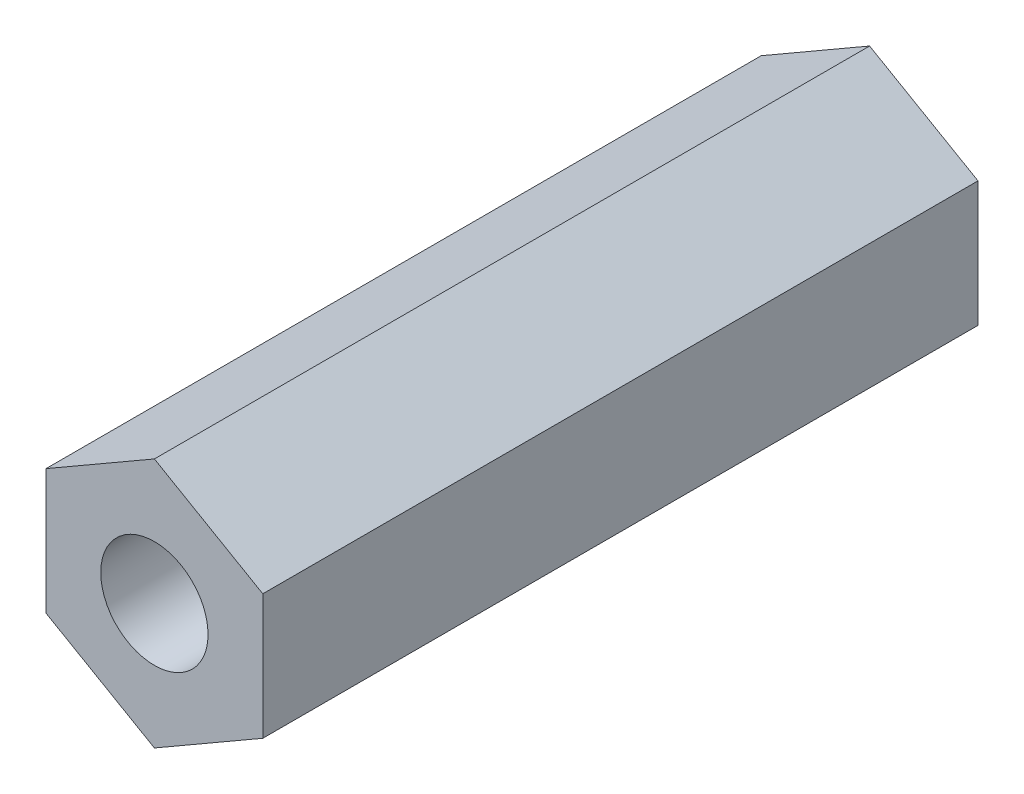
SolidWorks part; units mm, degrees
ref_plane "Front Plane" through (0, 0, 0) normal (0, 0, 1) x (1, 0, 0)
ref_plane "Top Plane" through (0, 0, 0) normal (0, 1, 0) x (1, 0, 0)
ref_plane "Right Plane" through (0, 0, 0) normal (1, 0, 0) x (0, 0, -1)
sketch "Sketch2" plane through (0, 0, 0) normal (0, 0, 1) x (1, 0, 0)
  line L1 (0, -3.5) -> (3.0311, -1.75)
  line L2 (3.0311, -1.75) -> (3.0311, 1.75)
  line L3 (3.0311, 1.75) -> (0, 3.5)
  line L4 (0, 3.5) -> (-3.0311, 1.75)
  line L5 (-3.0311, 1.75) -> (-3.0311, -1.75)
  line L6 (-3.0311, -1.75) -> (0, -3.5)
  circle A0 centre (0, 0) radius 3.0311 construction
  circle A1 centre (0, 0) radius 1.5
  dimension "D1" = 3
  dimension "D2" = 7
  dimension "D3" = 5.25
extrude "Boss-Extrude1" add sketch "Sketch2" along normal blind 20 contours L3 L4 L5 L6 L1 L2
sketch "Sketch3" plane through (0, 0, 0) normal (0, 0, -1) x (-1, 0, 0)
  circle A0 centre (0, 0) radius 1.5
  dimension "D1" = 3
extrude "Cut-Extrude1" cut sketch "Sketch3" against normal blind 20
